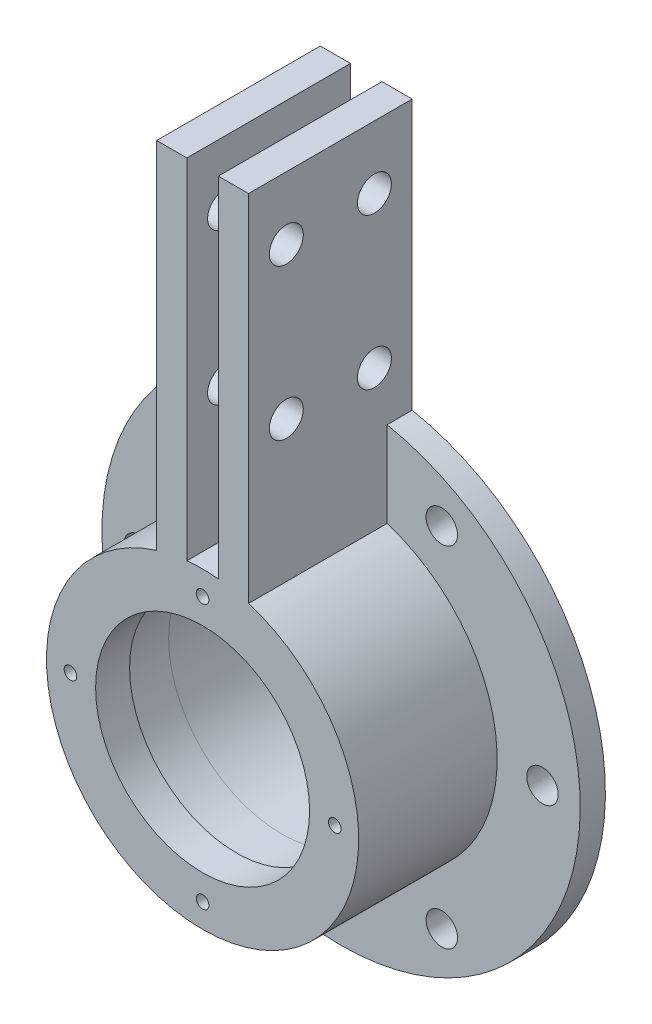
SolidWorks part; units mm, degrees
ref_plane "Front Plane" through (0, 0, 0) normal (0, 0, 1) x (1, 0, 0)
ref_plane "Top Plane" through (0, 0, 0) normal (0, 1, 0) x (1, 0, 0)
ref_plane "Right Plane" through (0, 0, 0) normal (1, 0, 0) x (0, 0, -1)
sketch "Sketch1" plane through (0, 0, 0) normal (0, 0, 1) x (1, 0, 0)
  line L1 (-18.25, 59.2532) -> (-18.25, 200.2532)
  line L2 (18.25, 59.2532) -> (18.25, 200.2532)
  line L3 (-18.25, 200.2532) -> (-6.25, 200.2532)
  line L4 (-6.25, 200.2532) -> (-6.25, 61.6842)
  line L5 (6.25, 200.2532) -> (6.25, 61.6842)
  line L6 (6.25, 200.2532) -> (18.25, 200.2532)
  circle A0 centre (0, 0) radius 42.5
  arc A2 (-18.25, 59.2532) -> (18.25, 59.2532) centre (0, 0) ccw
  arc A3 (6.25, 61.6842) -> (-6.25, 61.6842) centre (0, 0) ccw
  point P4 (0, 0)
  point P10 (0, 200.2532)
  point P13 (0, 0)
  dimension "D1" = 85
  dimension "D2" = 62
  dimension "D3" = 12
  dimension "D4" = 36.5
  dimension "D5" = 12
  dimension "D6" = 200.2532
  dimension "D7" = 141
extrude "Boss-Extrude1" add sketch "Sketch1" along normal blind 65
sketch "Sketch2" plane through (0, 0, 0) normal (0, 0, -1) x (-1, 0, 0)
  line L6 (6.25, 200.2532) -> (6.25, 61.6842)
  line L7 (-6.25, 61.6842) -> (-6.25, 200.2532)
  line L8 (-6.25, 200.2532) -> (-18.25, 200.2532)
  line L9 (-18.25, 200.2532) -> (-18.25, 59.2532)
  line L10 (18.25, 59.2532) -> (18.25, 200.2532)
  line L11 (18.25, 200.2532) -> (6.25, 200.2532)
  line L12 (6.25, 94.7942) -> (6.25, 61.6842)
  line L13 (-6.25, 61.6842) -> (-6.25, 94.7942)
  line L14 (-6.25, 200.2532) -> (-18.25, 200.2532)
  line L15 (-18.25, 93.2306) -> (-18.25, 59.2532)
  line L16 (18.25, 59.2532) -> (18.25, 93.2306)
  line L17 (18.25, 200.2532) -> (6.25, 200.2532)
  arc A0 (-6.25, 94.7942) -> (6.25, 94.7942) centre (0, 0) ccw
  arc A5 (6.25, 61.6842) -> (-6.25, 61.6842) centre (0, 0) ccw
  arc A6 (-18.25, 59.2532) -> (18.25, 59.2532) centre (0, 0) ccw
  arc A7 (6.25, 61.6842) -> (-6.25, 61.6842) centre (0, 0) ccw
  arc A8 (-18.25, 59.2532) -> (18.25, 59.2532) centre (0, 0) ccw
  point P6 (0, -95)
  line M10 (6.25, 200.2532) -> (6.25, 61.6842)
  arc M11 (6.25, 61.6842) -> (-6.25, 61.6842) centre (0, 0) ccw
  line M12 (-6.25, 61.6842) -> (-6.25, 200.2532)
  line M14 (-18.25, 200.2532) -> (-18.25, 59.2532)
  arc M15 (-18.25, 59.2532) -> (18.25, 59.2532) centre (0, 0) ccw
  line M16 (18.25, 59.2532) -> (18.25, 200.2532)
  circle M18 centre (0, 0) radius 42.5
  dimension "D1" = 190
  dimension "D2" = 0
extrude "Boss-Extrude2" add sketch "Sketch2" against normal blind 10 contours A0 M14 M16 M15 | A0 M16 M10 M11 M12 M14 M15 M18
sketch "Sketch3" plane through (0, 0, 0) normal (0, 0, -1) x (-1, 0, 0)
  circle A0 centre (0, 0) radius 45.05
  dimension "D1" = 90.1
extrude "Cut-Extrude1" cut sketch "Sketch3" against normal blind 33.5
sketch "Sketch4" plane through (0, 0, 33.5) normal (0, 0, -1) x (-1, 0, 0)
  circle A0 centre (0, 0) radius 44.9925
  dimension "D1" = 89.985
extrude "Cut-Extrude2" cut sketch "Sketch4" against normal blind 18
hole_wizard "Ø12.0mm Dowel Hole1" positions "Sketch6" profile "Sketch7" hole size "Ø12.0" standard "ISO" end condition up to next
sketch "Sketch6" plane through (0, 0, 0) normal (0, 0, -1) x (-1, 0, 0)
  circle A0 centre (0, 0) radius 80 construction
  point P10 (-80, 0)
  point P16 (-40, 69.282)
  point P17 (40, 69.282)
  point P18 (80, 0)
  point P19 (40, -69.282)
  point P20 (-40, -69.282)
  dimension "D1" = 160
  dimension "D2" = 6
sketch "Sketch7" plane through (40, -69.282, 0) normal (1, 0, 0) x (0, 1, 0)
  line L0 (0, 0) -> (0, 10)
  line L1 (0, 10) -> (6.25, 10)
  line L2 (6.25, 10) -> (6.25, 0)
  line L5 (6.25, 0) -> (0, 0)
  line L11 (0, -6.35) -> (0, 107.95) construction
  dimension "Thru Hole Dia." = 12.5
  dimension "Thru Hole Depth" = 10
hole_wizard "M6 Tapped Hole1" positions "Sketch8" profile "Sketch9" tap size "M6" standard "ISO"
sketch "Sketch8" plane through (0, 0, 65) normal (0, 0, 1) x (1, 0, 0)
  circle A0 centre (0, 0) radius 52.5 construction
  point P8 (-52.5, 0)
  point P10 (0, 52.5)
  point P12 (52.5, 0)
  point P14 (0, -52.5)
  dimension "D1" = 105
sketch "Sketch9" plane through (0, -52.5, 65) normal (1, 0, 0) x (0, -1, 0)
  line L0 (0, 0) -> (0, 13.5022)
  line L1 (0, 13.5022) -> (2.5, 12)
  line L2 (2.5, 12) -> (2.5, 0)
  line L5 (2.5, 0) -> (0, 0)
  line L10 (0, 13.5022) -> (-2.5, 12) construction
  line L11 (0, -6.35) -> (0, 107.95) construction
  dimension "Tap Drill Dia." = 5
  dimension "Tap Drill Depth" = 12
  dimension "Drill Angle" = 118
cosmetic thread "Hole Thread1" parameters "D1"=12, "D2"=6
cosmetic thread "Hole Thread2" parameters "D1"=12, "D2"=6
cosmetic thread "Hole Thread3" parameters "D1"=12, "D2"=6
cosmetic thread "Hole Thread4" parameters "D1"=12, "D2"=6
sketch "Sketch10" plane through (0, 0, 0) normal (0, 0, -1) x (-1, 0, 0)
  circle A0 centre (0, 0) radius 45.05 construction
  circle A1 centre (0, 0) radius 45.05
  circle A2 centre (0, 0) radius 52.5
  dimension "D1" = 105
extrude "Boss-Extrude3" add sketch "Sketch10" along normal blind 5
hole_wizard "Ø12.0mm Dowel Hole2" positions "Sketch12" profile "Sketch13" hole size "Ø12.0" standard "ISO" end condition through all
sketch "Sketch12" plane through (-18.25, 0, 0) normal (-1, 0, 0) x (0, 0, 1)
  line L0 (65, 200.2532) -> (0, 200.2532) construction
  line L1 (65, 200.2532) -> (65, 59.2532) construction
  line L2 (0, 200.2532) -> (0, 93.2306) construction
  point P0 (15, 175.2532)
  point P3 (50, 175.2532)
  point P5 (50, 115.2532)
  point P7 (15, 115.2532)
  point P10 (0, 0)
  point P11 (0, 0)
  point P12 (0, 0)
  point P23 (44.6568, 174.3372)
  dimension "D1" = 25
  dimension "D2" = 60
  dimension "D3" = 15
  dimension "D4" = 15
sketch "Sketch13" plane through (-18.25, 175.2532, 15) normal (0, 1, 0) x (0, 0, 1)
  line L0 (0, 0) -> (0, 113.25)
  line L1 (0, 113.25) -> (6.75, 113.25)
  line L2 (6.75, 113.25) -> (6.75, 0)
  line L5 (6.75, 0) -> (0, 0)
  line L11 (0, -6.35) -> (0, 107.95) construction
  dimension "Thru Hole Dia." = 13.5
  dimension "Thru Hole Depth" = 113.25
